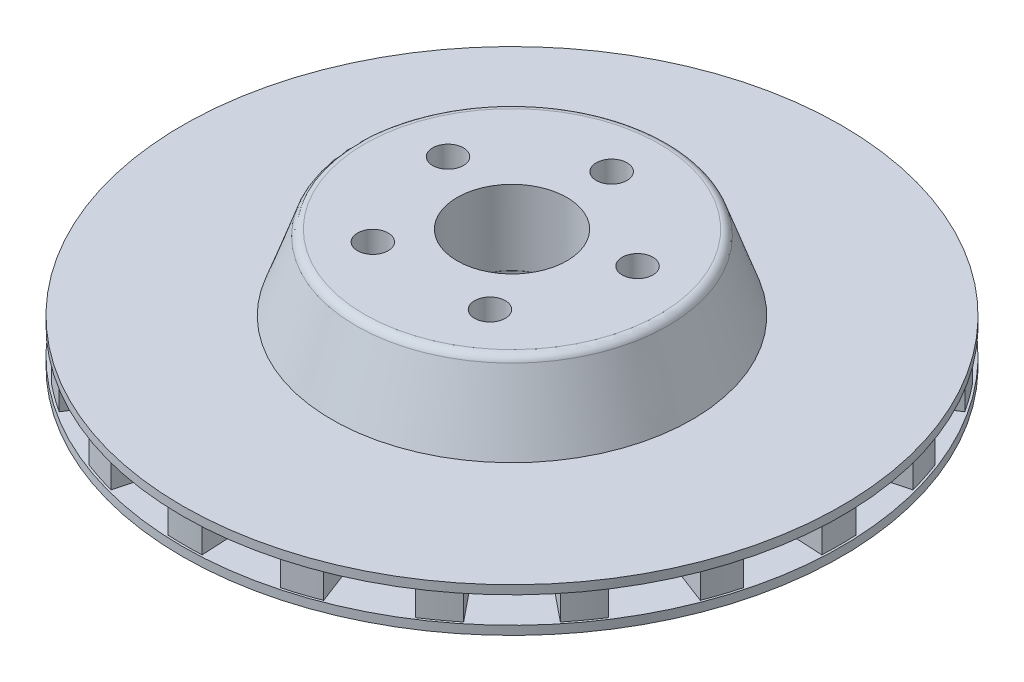
SolidWorks part; units mm, degrees
ref_plane "Front Plane" through (0, 0, 0) normal (0, 0, 1) x (1, 0, 0)
ref_plane "Top Plane" through (0, 0, 0) normal (0, 1, 0) x (1, 0, 0)
ref_plane "Right Plane" through (0, 0, 0) normal (1, 0, 0) x (0, 0, -1)
sketch "Sketch1" plane through (0, 0, 0) normal (0, 1, 0) x (1, 0, 0)
  circle A0 centre (0, 0) radius 150
  dimension "D1" = 300
extrude "Boss-Extrude1" add sketch "Sketch1" along normal blind 4
sketch "Sketch2" plane through (0, 4, 0) normal (0, 1, 0) x (1, 0, 0)
  line L0 (0, 164.5803) -> (0, -149) construction
  line L1 (-4.2915, 81.8876) -> (-7.7981, 148.7958)
  line L2 (4.2915, 81.8876) -> (7.7981, 148.7958)
  line L3 (21.2232, 79.2059) -> (38.564, 143.9229)
  line L4 (29.3862, 76.5536) -> (53.3968, 139.1035)
  line L5 (44.6604, 68.771) -> (81.1512, 124.9619)
  line L6 (51.6043, 63.726) -> (93.7687, 115.7947)
  line L7 (63.726, 51.6043) -> (115.7947, 93.7687)
  line L8 (68.771, 44.6604) -> (124.9619, 81.1512)
  line L9 (76.5536, 29.3862) -> (139.1035, 53.3968)
  line L10 (79.2059, 21.2232) -> (143.9229, 38.564)
  line L11 (81.8876, 4.2915) -> (148.7958, 7.7981)
  line L12 (81.8876, -4.2915) -> (148.7958, -7.7981)
  line L13 (79.2059, -21.2232) -> (143.9229, -38.564)
  line L14 (76.5536, -29.3862) -> (139.1035, -53.3968)
  line L15 (68.771, -44.6604) -> (124.9619, -81.1512)
  line L16 (63.726, -51.6043) -> (115.7947, -93.7687)
  line L17 (51.6043, -63.726) -> (93.7687, -115.7947)
  line L18 (44.6604, -68.771) -> (81.1512, -124.9619)
  line L19 (29.3862, -76.5536) -> (53.3968, -139.1035)
  line L20 (21.2232, -79.2059) -> (38.564, -143.9229)
  line L21 (4.2915, -81.8876) -> (7.7981, -148.7958)
  line L22 (-4.2915, -81.8876) -> (-7.7981, -148.7958)
  line L23 (-21.2232, -79.2059) -> (-38.564, -143.9229)
  line L24 (-29.3862, -76.5536) -> (-53.3968, -139.1035)
  line L25 (-44.6604, -68.771) -> (-81.1512, -124.9619)
  line L26 (-51.6043, -63.726) -> (-93.7687, -115.7947)
  line L27 (-63.726, -51.6043) -> (-115.7947, -93.7687)
  line L28 (-68.771, -44.6604) -> (-124.9619, -81.1512)
  line L29 (-76.5536, -29.3862) -> (-139.1035, -53.3968)
  line L30 (-79.2059, -21.2232) -> (-143.9229, -38.564)
  line L31 (-81.8876, -4.2915) -> (-148.7958, -7.7981)
  line L32 (-81.8876, 4.2915) -> (-148.7958, 7.7981)
  line L33 (-79.2059, 21.2232) -> (-143.9229, 38.564)
  line L34 (-76.5536, 29.3862) -> (-139.1035, 53.3968)
  line L35 (-68.771, 44.6604) -> (-124.9619, 81.1512)
  line L36 (-63.726, 51.6043) -> (-115.7947, 93.7687)
  line L37 (-51.6043, 63.726) -> (-93.7687, 115.7947)
  line L38 (-44.6604, 68.771) -> (-81.1512, 124.9619)
  line L39 (-29.3862, 76.5536) -> (-53.3968, 139.1035)
  line L40 (-21.2232, 79.2059) -> (-38.564, 143.9229)
  arc A0 (-81.8876, 4.2915) -> (-81.8876, -4.2915) centre (0, 0) ccw
  arc A1 (-81.1512, 124.9619) -> (-93.7687, 115.7947) centre (0, 0) ccw
  arc A2 (-76.5536, 29.3862) -> (-79.2059, 21.2232) centre (0, 0) ccw
  arc A3 (-63.726, 51.6043) -> (-68.771, 44.6604) centre (0, 0) ccw
  arc A4 (-44.6604, 68.771) -> (-51.6043, 63.726) centre (0, 0) ccw
  arc A5 (-21.2232, 79.2059) -> (-29.3862, 76.5536) centre (0, 0) ccw
  arc A6 (-29.3862, -76.5536) -> (-21.2232, -79.2059) centre (0, 0) ccw
  arc A7 (-51.6043, -63.726) -> (-44.6604, -68.771) centre (0, 0) ccw
  arc A8 (-68.771, -44.6604) -> (-63.726, -51.6043) centre (0, 0) ccw
  arc A9 (-79.2059, -21.2232) -> (-76.5536, -29.3862) centre (0, 0) ccw
  arc A10 (-4.2915, -81.8876) -> (4.2915, -81.8876) centre (0, 0) ccw
  arc A11 (21.2232, -79.2059) -> (29.3862, -76.5536) centre (0, 0) ccw
  arc A12 (44.6604, -68.771) -> (51.6043, -63.726) centre (0, 0) ccw
  arc A13 (63.726, -51.6043) -> (68.771, -44.6604) centre (0, 0) ccw
  arc A14 (76.5536, -29.3862) -> (79.2059, -21.2232) centre (0, 0) ccw
  arc A15 (81.8876, -4.2915) -> (81.8876, 4.2915) centre (0, 0) ccw
  arc A16 (79.2059, 21.2232) -> (76.5536, 29.3862) centre (0, 0) ccw
  arc A17 (68.771, 44.6604) -> (63.726, 51.6043) centre (0, 0) ccw
  arc A18 (51.6043, 63.726) -> (44.6604, 68.771) centre (0, 0) ccw
  arc A19 (29.3862, 76.5536) -> (21.2232, 79.2059) centre (0, 0) ccw
  arc A20 (4.2915, 81.8876) -> (-4.2915, 81.8876) centre (0, 0) ccw
  arc A21 (-115.7947, 93.7687) -> (-124.9619, 81.1512) centre (0, 0) ccw
  arc A22 (-139.1035, 53.3968) -> (-143.9229, 38.564) centre (0, 0) ccw
  arc A23 (-148.7958, 7.7981) -> (-148.7958, -7.7981) centre (0, 0) ccw
  arc A24 (-143.9229, -38.564) -> (-139.1035, -53.3968) centre (0, 0) ccw
  arc A25 (-124.9619, -81.1512) -> (-115.7947, -93.7687) centre (0, 0) ccw
  arc A26 (-38.564, 143.9229) -> (-53.3968, 139.1035) centre (0, 0) ccw
  arc A27 (7.7981, 148.7958) -> (-7.7981, 148.7958) centre (0, 0) ccw
  arc A28 (53.3968, 139.1035) -> (38.564, 143.9229) centre (0, 0) ccw
  arc A29 (93.7687, 115.7947) -> (81.1512, 124.9619) centre (0, 0) ccw
  arc A30 (124.9619, 81.1512) -> (115.7947, 93.7687) centre (0, 0) ccw
  arc A31 (143.9229, 38.564) -> (139.1035, 53.3968) centre (0, 0) ccw
  arc A32 (148.7958, -7.7981) -> (148.7958, 7.7981) centre (0, 0) ccw
  arc A33 (139.1035, -53.3968) -> (143.9229, -38.564) centre (0, 0) ccw
  arc A34 (115.7947, -93.7687) -> (124.9619, -81.1512) centre (0, 0) ccw
  arc A35 (81.1512, -124.9619) -> (93.7687, -115.7947) centre (0, 0) ccw
  arc A36 (38.564, -143.9229) -> (53.3968, -139.1035) centre (0, 0) ccw
  arc A37 (-7.7981, -148.7958) -> (7.7981, -148.7958) centre (0, 0) ccw
  arc A38 (-53.3968, -139.1035) -> (-38.564, -143.9229) centre (0, 0) ccw
  arc A39 (-93.7687, -115.7947) -> (-81.1512, -124.9619) centre (0, 0) ccw
  point P87 (0, 0)
  dimension "D1" = 164
  dimension "D2" = 298
  dimension "D3" = 3
  dimension "D4" = 20
extrude "Boss-Extrude3" add sketch "Sketch2" along normal blind 12
sketch "Sketch4" plane through (0, 16, 0) normal (0, 1, 0) x (1, 0, 0)
  circle A0 centre (0, 0) radius 150
  dimension "D1" = 300
extrude "Boss-Extrude4" add sketch "Sketch4" along normal blind 4
sketch "Sketch5" plane through (0, 0, 0) normal (0, 0, 1) x (1, 0, 0)
  line L0 (0, 54.0887) -> (0, 0.6091) construction
  line L1 (0, 20.0887) -> (-82, 20)
  line L2 (0, 20.0887) -> (0, 54.0887)
  line L3 (0, 54.0887) -> (-70, 54.0887)
  line L4 (-70, 54.0887) -> (-82, 20)
  dimension "D1" = 82
  dimension "D2" = 34
  dimension "D3" = 70
  dimension "D4" = 70.545
revolve "Revolve1" add sketch "Sketch5" angle 360 about L0
fillet "Fillet1" radius 4 1 edges at (0, 54.0887, 70)
sketch "Sketch6" plane through (0, 54.0887, 0) normal (0, 1, 0) x (1, 0, 0)
  circle A0 centre (0, 0) radius 25
  dimension "D1" = 50
extrude "Cut-Extrude1" cut sketch "Sketch6" against normal through all
sketch "Sketch7" plane through (0, 54.0887, 0) normal (0, 1, 0) x (1, 0, 0)
  circle A0 centre (0, 45.3494) radius 7
  circle A1 centre (43.1299, 14.0137) radius 7
  circle A2 centre (26.6557, -36.6885) radius 7
  circle A3 centre (-26.6557, -36.6885) radius 7
  circle A4 centre (-43.1299, 14.0137) radius 7
  point P12 (0, 0)
  dimension "D1" = 14
  dimension "D2" = 5
extrude "Cut-Extrude2" cut sketch "Sketch7" against normal blind 31
